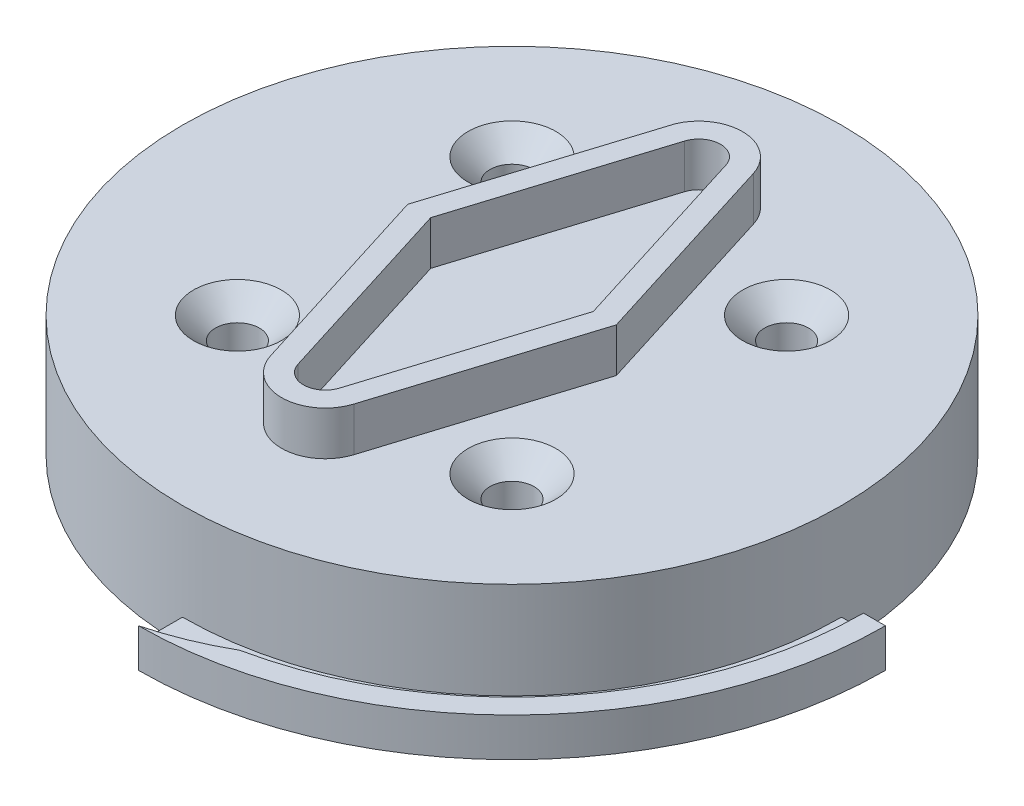
SolidWorks part; units mm, degrees
ref_plane "前视基准面" through (0, 0, 0) normal (0, 0, 1) x (1, 0, 0)
ref_plane "上视基准面" through (0, 0, 0) normal (0, 1, 0) x (1, 0, 0)
ref_plane "右视基准面" through (0, 0, 0) normal (1, 0, 0) x (0, 0, -1)
sketch "草图1" plane through (0, 0, 0) normal (0, 1, 0) x (1, 0, 0)
  circle A0 centre (0, 0) radius 30
extrude "凸台-拉伸1" add sketch "草图1" along normal blind 11
sketch "草图3" plane through (0, 0, 0) normal (0, -1, 0) x (1, 0, 0)
  line L0 (-34, 0) -> (-30, 0)
  line L1 (0, -34) -> (0, -30)
  line L3 (0, 34) -> (0, 30)
  line L4 (34, 0) -> (30, 0)
  arc A0 (-34, 0) -> (0, -34) centre (0, 0) ccw
  circle A1 centre (0, 0) radius 30 construction
  arc A2 (-30, 0) -> (0, -30) centre (0, 0) ccw
  arc A3 (0, 34) -> (34, 0) centre (0, 0) cw
  arc A4 (0, 30) -> (30, 0) centre (0, 0) cw
  dimension "D1" = 34
extrude "凸台-拉伸2" add sketch "草图3" against normal blind 4
ref_axis "基准轴1" through (0, 0, 0) along (0, 1, 0)
sketch "草图6" plane through (0, 0, 0) normal (0, 0, -1) x (-1, 0, 0)
  line L1 (-30, 2.2) -> (-32, 2.2)
  line L2 (-32, 2.2) -> (-32, 3.52)
  line L3 (-32, 3.52) -> (-34, 3.52)
  line L4 (-34, 4) -> (-34, 0) construction
  line L5 (-34, 3.52) -> (-34, 4)
  line L6 (-34, 4) -> (-30, 4)
  line L7 (-30, 4) -> (-30, 2.2)
  dimension "D1" = 3.52
  dimension "D2" = 2
  dimension "D3" = 1.32
revolve "切除-旋转8" cut sketch "草图6" angle 360 about axis through (0, 0, 0) along (0, 1, 0)
sketch "草图7" plane through (0, 3.52, 0) normal (0, 1, 0) x (1, 0, 0)
  line L0 (6.5224, -31.3282) -> (-2.1919, -31.4445)
  line L1 (-2.1919, -31.4445) -> (0, -34)
  line L2 (-6.5224, 31.3282) -> (2.581, 31.0313)
  line L3 (2.581, 31.0313) -> (0, 34)
  arc A0 (0, 34) -> (-6.5224, 31.3282) centre (6.8858, 7.8928) ccw
  arc A1 (0, 32) -> (-32, 0) centre (0, 0) ccw construction
  arc A2 (0, -34) -> (6.5224, -31.3282) centre (-6.8858, -7.8928) ccw
  arc A3 (0, -32) -> (32, 0) centre (0, 0) ccw construction
extrude "切除-拉伸1" cut sketch "草图7" against normal blind 1.32
sketch "草图8" plane through (0, 11, 0) normal (0, 1, 0) x (1, 0, 0)
  line L0 (-30, 0) -> (-30, 30)
  line L1 (-30, 30) -> (30, 30)
  line L2 (30, 30) -> (30, -30)
  line L3 (30, -30) -> (-30, -30)
  line L4 (-30, -30) -> (-30, 0)
  line L5 (-30, 0) -> (-12.5, 0)
  line L6 (-2.7365, 12.5) -> (-30, 12.5)
  line L7 (-2.7365, 30) -> (-2.7365, 12.5)
  line L8 (-12.5, 0) -> (-12.5, 30)
  line L9 (-12.5, 0) -> (-12.5, -30)
  line L10 (0, -30) -> (0, -12.5)
  line L11 (-30, -12.5) -> (30, -12.5)
  line L12 (30, 0) -> (12.5, 0)
  line L13 (12.5, 30) -> (12.5, -30)
  circle A1 centre (-12.5, 12.5) radius 2
  circle A2 centre (-12.5, -12.5) radius 2
  circle A3 centre (12.5, 12.5) radius 2
  circle A4 centre (12.5, -12.5) radius 2
  dimension "D3" = 17.5
  dimension "D4" = 17.5
  dimension "D5" = 4
  dimension "D6" = 4
  dimension "D7" = 4
  dimension "D8" = 4
  dimension "D1" = 17.5
  dimension "D2" = 17.5
extrude "切除-拉伸2" cut sketch "草图8" against normal through all contours L13 A3 | L13 A3 | L11 A2 L9 | L9 A2 L11 | L11 A2 L9 | L9 A2 L11 | A4 | A1
chamfer "倒角2" distance 2 angle 45 4 edges at (-12.5, 11, 14.5) (12.5, 11, 14.5) (12.5, 11, -10.5) (-12.5, 11, -10.5)
sketch "草图13" plane through (0, 11, 0) normal (0, 1, 0) x (1, 0, 0)
  line L0 (-7.4, 0) -> (-1.8895, -17.5919)
  line L1 (-7.4, 0) -> (-1.8895, 17.5919)
  line L2 (7.4, 0) -> (1.8895, 17.5919)
  line L3 (7.4, 0) -> (1.8895, -17.5919)
  line L4 (-9.5, 0) -> (-3.7978, -18.1905)
  line L5 (-9.5, 0) -> (-3.6599, 18.5638)
  line L6 (9.5, 0) -> (3.7978, 18.1905)
  line L7 (9.5, 0) -> (3.7978, -18.1905)
  arc A0 (1.8895, 17.5919) -> (-1.8895, 17.5919) centre (0, 17) ccw
  arc A1 (-1.8895, -17.5919) -> (1.8895, -17.5919) centre (0, -17) ccw
  arc A3 (-3.7978, -18.1905) -> (3.7978, -18.1905) centre (0, -17) ccw
  arc A6 (3.7978, 18.1905) -> (-3.896, 17.8132) centre (0, 17) ccw
  point P3 (0, 0)
  point P16 (0, 0)
  dimension "D1" = 14.8
  dimension "D2" = 19
extrude "凸台-拉伸4" add sketch "草图13" along normal blind 4 contours L6 A6 L5 L4 A3 L7 A1 L0 L1 A0 L2 L3
